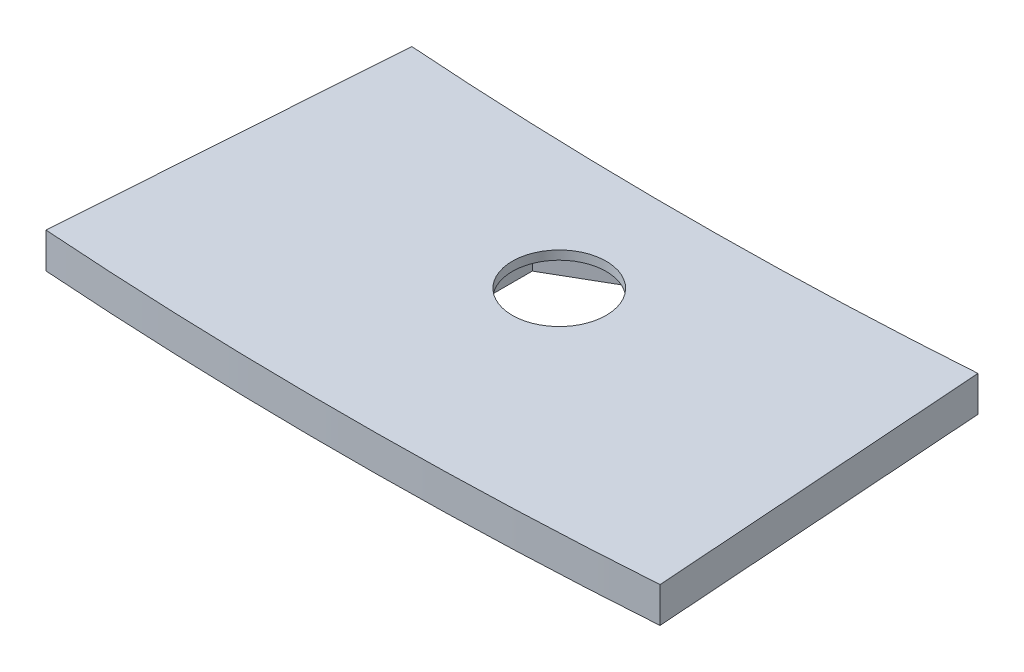
SolidWorks part; units mm, degrees
ref_plane "Front Plane" through (0, 0, 0) normal (0, 0, 1) x (1, 0, 0)
ref_plane "Top Plane" through (0, 0, 0) normal (0, 1, 0) x (1, 0, 0)
ref_plane "Right Plane" through (0, 0, 0) normal (1, 0, 0) x (0, 0, -1)
sketch "BASE" plane through (0, 0, 0) normal (0, 1, 0) x (1, 0, 0)
  line L0 (0, 0) -> (0, -243.5) construction
  line L1 (15.9742, -228.4422) -> (16.9857, -242.9068)
  line L2 (-15.9742, -228.4422) -> (-16.9857, -242.9068)
  line L3 (0, 0) -> (15.9742, -228.4422) construction
  line L4 (0, 0) -> (-15.9742, -228.4422) construction
  line L5 (0, -229) -> (0, -243.5) construction
  line L7 (-10, -226.25) -> (10, -226.25) construction
  line L8 (-10, -226.25) -> (-10, -246.25) construction
  line L9 (-10, -246.25) -> (10, -246.25) construction
  line L10 (10, -226.25) -> (10, -246.25) construction
  line L11 (-10, -226.25) -> (10, -246.25) construction
  line L12 (-10, -246.25) -> (10, -226.25) construction
  arc A0 (-16.9857, -242.9068) -> (16.9857, -242.9068) centre (0, 0) ccw
  arc A1 (-15.9742, -228.4422) -> (15.9742, -228.4422) centre (0, 0) ccw
  circle A2 centre (0, -236.25) radius 2.65
  point P14 (0, 0)
  dimension "D1" = 487
  dimension "D2" = 14.5
  dimension "D6" = 5.3
  dimension "D3" = 4
  dimension "D4" = 4
  dimension "D5" = 20
sketch "Sketch2" plane through (0, 0, 0) normal (0, 1, 0) x (1, 0, 0)
  line L1 (-15.9742, -228.4422) -> (-16.9857, -242.9068) construction
  line L3 (15.9742, -228.4422) -> (16.9857, -242.9068) construction
  line L4 (0, 0) -> (-17.3345, -247.8947) construction
  line L5 (0, 0) -> (17.3345, -247.8947) construction
  line L6 (-15.9847, -228.5918) -> (-17.3345, -247.8947)
  line L7 (15.9847, -228.5918) -> (17.3345, -247.8947)
  arc A0 (15.9847, -228.5918) -> (-15.9847, -228.5918) centre (0, 0) cw
  arc A1 (-15.9742, -228.4422) -> (15.9742, -228.4422) centre (0, 0) ccw construction
  arc A2 (17.3345, -247.8947) -> (-17.3345, -247.8947) centre (0, 0) cw
  arc A3 (-16.9857, -242.9068) -> (16.9857, -242.9068) centre (0, 0) ccw construction
  circle A4 centre (0, -236.25) radius 2.65
  dimension "D1" = 0.15
  dimension "D2" = 5
  dimension "D3" = 5.3
extrude "Boss-Extrude1" add sketch "Sketch2" along normal blind 2
sketch "Sketch3" plane through (0, 0, 0) normal (0, 1, 0) x (1, 0, 0)
  line L0 (-10, -226.25) -> (10, -246.25) construction
  line L1 (0, -240.4069) -> (3.6, -238.3285)
  line L2 (3.6, -238.3285) -> (3.6, -234.1715)
  line L3 (3.6, -234.1715) -> (0, -232.0931)
  line L4 (0, -232.0931) -> (-3.6, -234.1715)
  line L5 (-3.6, -234.1715) -> (-3.6, -238.3285)
  line L6 (-3.6, -238.3285) -> (0, -240.4069)
  circle A0 centre (0, -236.25) radius 3.6 construction
extrude "Cut-Extrude1" cut sketch "Sketch3" along normal blind 1.5
